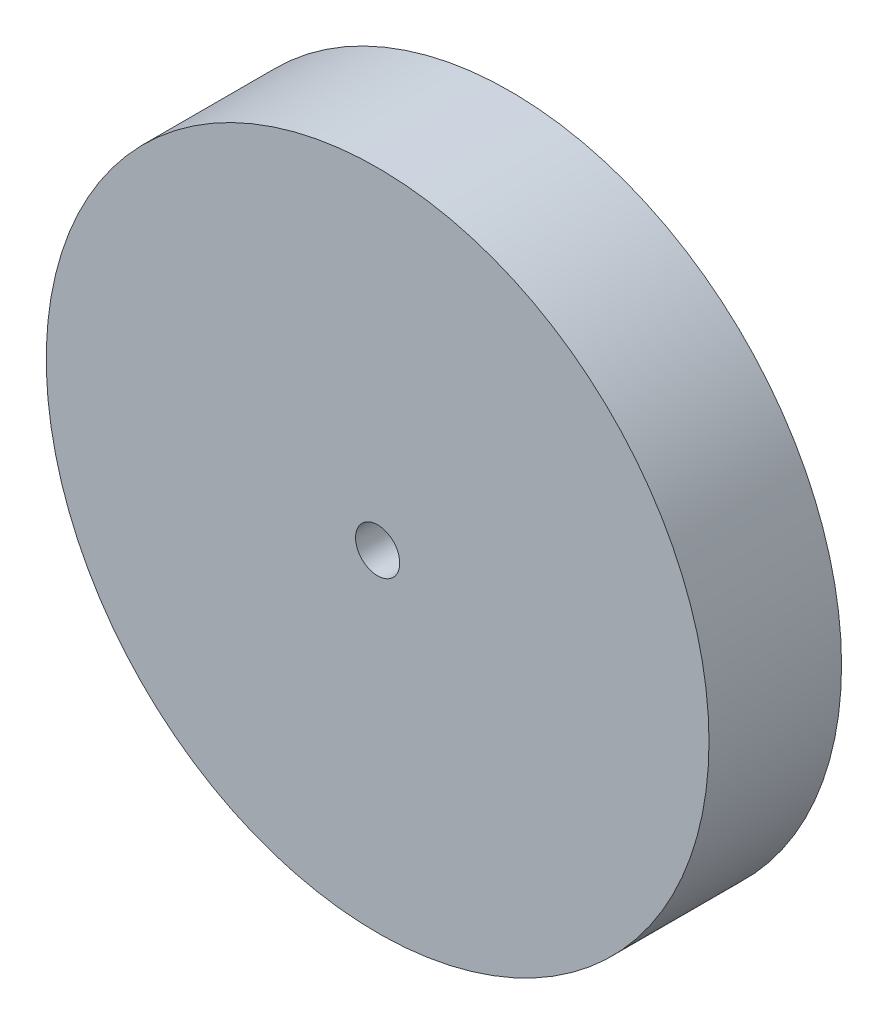
SolidWorks part; units mm, degrees
ref_plane "前视基准面" through (0, 0, 0) normal (0, 0, 1) x (1, 0, 0)
ref_plane "上视基准面" through (0, 0, 0) normal (0, 1, 0) x (1, 0, 0)
ref_plane "右视基准面" through (0, 0, 0) normal (1, 0, 0) x (0, 0, -1)
sketch "草图1" plane through (0, 0, 0) normal (0, 0, 1) x (1, 0, 0)
  circle A0 centre (0, 0) radius 75
  circle A1 centre (0, 0) radius 5
  dimension "D1" = 150
extrude "凸台-拉伸1" add sketch "草图1" along normal blind 30
